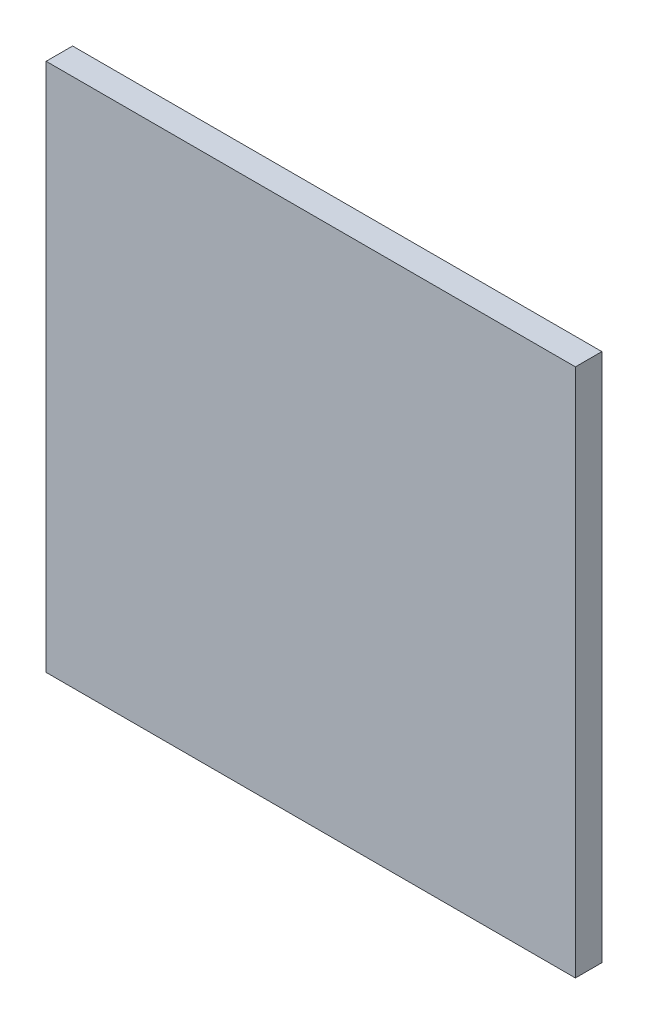
SolidWorks part; units mm, degrees
ref_plane "Front Plane" through (0, 0, 0) normal (0, 0, 1) x (1, 0, 0)
ref_plane "Top Plane" through (0, 0, 0) normal (0, 1, 0) x (1, 0, 0)
ref_plane "Right Plane" through (0, 0, 0) normal (1, 0, 0) x (0, 0, -1)
sketch "Sketch1" plane through (0, 0, 0) normal (0, 0, 1) x (1, 0, 0)
  line L1 (0, 0) -> (100, 0)
  line L2 (0, 0) -> (0, 100)
  line L3 (0, 100) -> (100, 100)
  line L4 (100, 0) -> (100, 100)
  dimension "D1" = 100
extrude "Boss-Extrude1" add sketch "Sketch1" along normal blind 5
